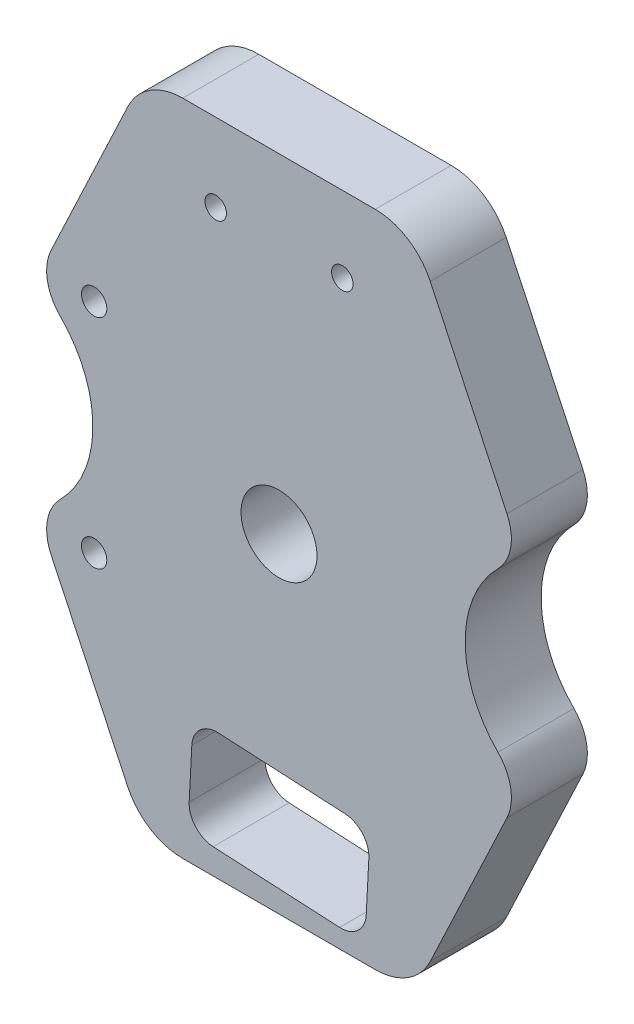
SolidWorks part; units mm, degrees
ref_plane "Płaszczyzna przednia" through (0, 0, 0) normal (0, 0, 1) x (1, 0, 0)
ref_plane "Płaszczyzna górna" through (0, 0, 0) normal (0, 1, 0) x (1, 0, 0)
ref_plane "Płaszczyzna prawa" through (0, 0, 0) normal (1, 0, 0) x (0, 0, -1)
sketch "Szkic1" plane through (0, 0, 0) normal (0, 0, 1) x (1, 0, 0)
  line L3 (0, 260) -> (0, 0) construction
  line L5 (0, 130) -> (-92.5, 130) construction
  line L6 (25, 230) -> (-113.1637, 230) construction
  line L7 (-38, 260) -> (38, 260)
  line L8 (59.7094, 246.2323) -> (90.0082, 181.9488)
  line L9 (59.7662, 13.7409) -> (90.0082, 77.9041)
  line L10 (0, 0) -> (38, 0)
  line L11 (-59.7662, 13.7409) -> (-90.0082, 77.9041)
  line L12 (-59.7094, 246.2323) -> (-90.0082, 181.9488)
  line L13 (-38, 0) -> (0, 0)
  line L14 (25, 230) -> (-114.4641, 227.5656) construction
  line L15 (-25, 30) -> (78.9798, 30) construction
  line L16 (-25, 30) -> (79.6859, 24.5136) construction
  circle A0 centre (0, 130) radius 15
  circle A2 centre (-73, 87) radius 5
  circle A3 centre (-73, 173) radius 5
  arc A4 (86.4422, 161.3009) -> (86.4422, 98.552) centre (118, 129.9265) ccw
  circle A5 centre (25, 230) radius 50 construction
  arc A6 (86.4422, 98.552) -> (90.0082, 77.9041) centre (73.5, 85.6849) cw
  arc A7 (86.4422, 161.3009) -> (90.0082, 181.9488) centre (73.5, 174.168) ccw
  circle A8 centre (25, 230) radius 4.25
  arc A9 (59.7094, 246.2323) -> (38, 260) centre (38, 236) ccw
  arc A11 (59.7662, 13.7409) -> (38, 0) centre (38.0693, 23.9999) cw
  arc A12 (-59.7662, 13.7409) -> (-38, 0) centre (-38.0693, 23.9999) ccw
  arc A13 (-86.4422, 98.552) -> (-90.0082, 77.9041) centre (-73.5, 85.6849) ccw
  arc A14 (-86.4422, 161.3009) -> (-86.4422, 98.552) centre (-118, 129.9265) cw
  arc A15 (-86.4422, 161.3009) -> (-90.0082, 181.9488) centre (-73.5, 174.168) cw
  arc A16 (-59.7094, 246.2323) -> (-38, 260) centre (-38, 236) cw
  circle A18 centre (-24.9924, 229.1274) radius 4.25
  circle A20 centre (-25, 30) radius 4.25
  circle A21 centre (-25, 30) radius 50 construction
  circle A22 centre (24.9315, 27.3832) radius 4.25
  point P23 (96.4639, 168.868)
  dimension "D1" = 18.25
  dimension "D2" = 30
  dimension "D3" = 1
  dimension "D6" = 44.5
  dimension "D7" = 10
  dimension "D10" = 38
  dimension "D4" = 24
  dimension "D11" = 48
  dimension "D12" = 130
  dimension "D13" = 73.5
  dimension "D16" = 73
  dimension "D17" = 8.5
  dimension "D18" = 118
  dimension "D5" = 8.5
  dimension "D19" = 100
  dimension "D20" = 3
  dimension "D21" = 8.5
  dimension "D22" = 8.5
  dimension "D23" = 30
  dimension "D24" = 27.3832
  dimension "D25" = 25
  dimension "D26" = 100
  dimension "D8" = 25
  dimension "D9" = 30
  dimension "D14" = 73.5
  dimension "D15" = 43
extrude "Dodanie-wyciągnięcie1" add sketch "Szkic1" along normal blind 30
sketch "Szkic2" plane through (0, 0, 30) normal (0, 0, 1) x (1, 0, 0)
  line L1 (0, 260) -> (0, -13.2421) construction
  line L2 (38, 260) -> (-38, 260) construction
  line L12 (-88.8511, 130) -> (90.6766, 130) construction
  point P4 (0, 230)
  point P19 (0, 245)
sketch "Szkic3" plane through (0, 0, 0) normal (0, 0, -1) x (-1, 0, 0)
  circle A0 centre (25, 30) radius 4
  circle A1 centre (-24.9315, 27.3832) radius 4
  circle A2 centre (24.9924, 229.1274) radius 4
  circle A3 centre (-25, 230) radius 4
ref_plane "Płaszczyzna1" through (-86.4422, 98.552, 0) normal (0, 0, -1) x (-1, 0, 0)
sketch "Szkic4" plane through (-86.4422, 98.552, 0) normal (0, 0, -1) x (-1, 0, 0)
  line L0 (-52.5369, -48.0578) -> (-50.4435, -88.003)
  line L1 (-122.441, -51.7213) -> (-120.3475, -91.6665)
  line L2 (-86.4422, 161.448) -> (-86.4422, -111.7941) construction
  line L3 (-122.441, -51.7213) -> (-52.5369, -48.0578)
  line L4 (-121.3943, -71.6939) -> (-51.4902, -68.0304) construction
  line L5 (-50.4435, -88.003) -> (-120.3475, -91.6665)
  point P2 (-51.4902, -68.0304)
  point P9 (-121.3943, -71.6939)
  point P13 (-86.4422, -69.8622)
  dimension "D1" = 70
  dimension "D2" = 40
extrude "Wytnij-wyciągnięcie1" cut sketch "Szkic4" against normal blind 30
fillet "Zaokrąglenie1" radius 10 4 edges at (33.9053, 6.8855, 15) (-35.9988, 10.549, 15) (-33.9053, 50.4942, 15) (35.9988, 46.8306, 15)
sketch "Szkic5" plane through (0, 0, 0) normal (0, 0, -1) x (-1, 0, 0)
  line L0 (1.5036, 0) -> (-1.415, 55.6904)
  line L1 (23.919, 49.9708) -> (-26.0125, 47.354) construction
  line L2 (-23.919, 7.4088) -> (26.0125, 10.0256) construction
  line L3 (38, 0) -> (-38, 0) construction
  point P6 (-3.9004, 4.2504)
  point P7 (-1.0467, 48.6624)
  point P8 (-2.0916, 68.5995)
  point P9 (1.5036, 0)
  point P12 (-1.415, 55.6904)
